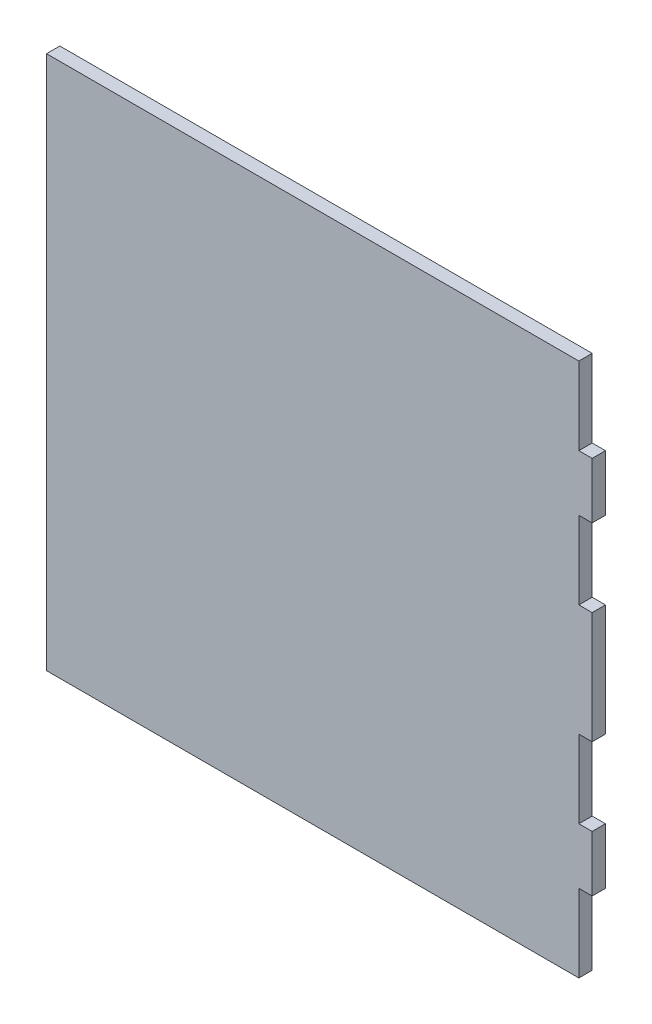
SolidWorks part; units mm, degrees
ref_plane "Front Plane" through (0, 0, 0) normal (0, 0, 1) x (1, 0, 0)
ref_plane "Top Plane" through (0, 0, 0) normal (0, 1, 0) x (1, 0, 0)
ref_plane "Right Plane" through (0, 0, 0) normal (1, 0, 0) x (0, 0, -1)
sketch "Sketch1" plane through (0, 0, 0) normal (0, 0, 1) x (1, 0, 0)
  line L0 (-163.9726, -220.3333) -> (-163.9726, -255.3333)
  line L1 (-163.9726, -160.1085) -> (-403.9726, -160.1085)
  line L2 (-163.9726, -160.1085) -> (-163.9726, -195.1085)
  line L3 (-163.9726, -401.0078) -> (-403.9726, -401.0078)
  line L4 (-403.9726, -160.1085) -> (-403.9726, -401.0078)
  line L5 (-163.9726, -340.7829) -> (-157.9726, -340.7829)
  line L7 (-163.9726, -366.0078) -> (-157.9726, -366.0078)
  line L8 (-157.9726, -340.7829) -> (-157.9726, -366.0078)
  line L9 (-163.9726, -255.3333) -> (-157.9726, -255.3333)
  line L11 (-163.9726, -305.7829) -> (-157.9726, -305.7829)
  line L12 (-157.9726, -255.3333) -> (-157.9726, -305.7829)
  line L13 (-163.9726, -195.1085) -> (-157.9726, -195.1085)
  line L15 (-163.9726, -220.3333) -> (-157.9726, -220.3333)
  line L16 (-157.9726, -195.1085) -> (-157.9726, -220.3333)
  line L17 (-163.9726, -305.7829) -> (-163.9726, -340.7829)
  line L18 (-163.9726, -366.0078) -> (-163.9726, -401.0078)
  dimension "D1" = 240
extrude "Boss-Extrude1" add sketch "Sketch1" along normal blind 6
